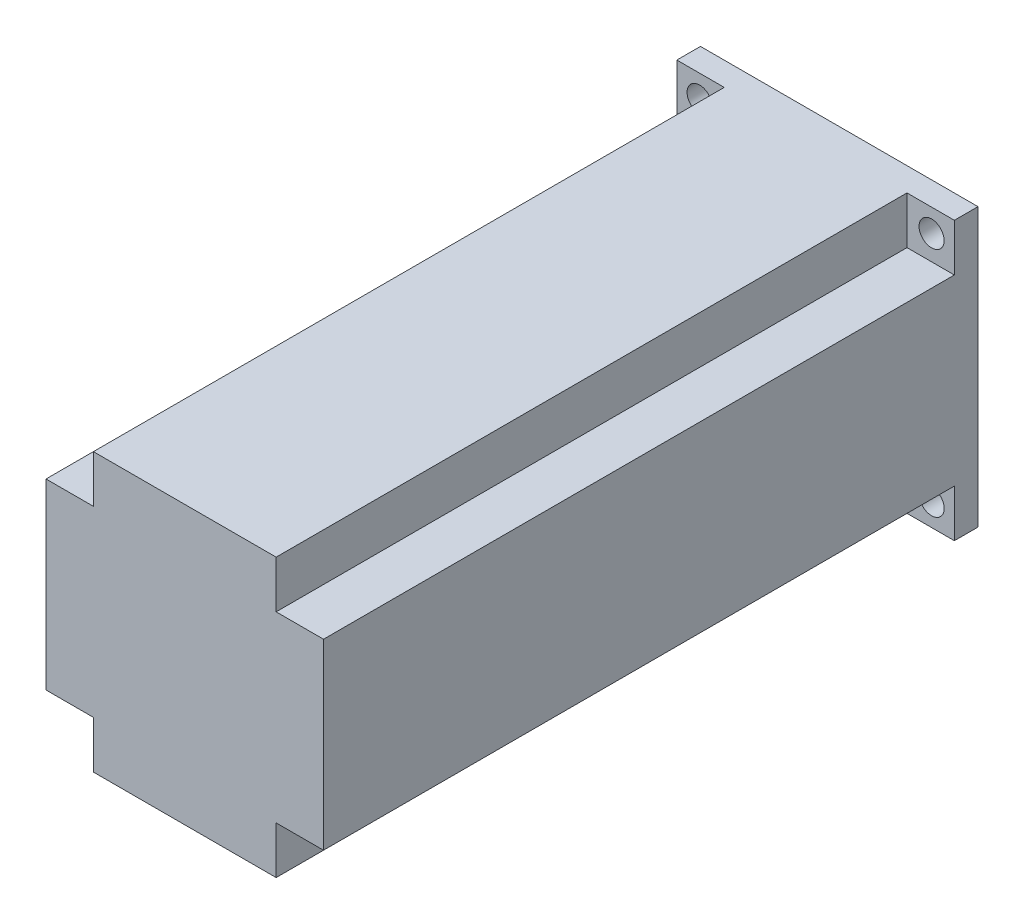
SolidWorks part; units mm, degrees
ref_plane "前视基准面" through (0, 0, 0) normal (0, 0, 1) x (1, 0, 0)
ref_plane "上视基准面" through (0, 0, 0) normal (0, 1, 0) x (1, 0, 0)
ref_plane "右视基准面" through (0, 0, 0) normal (1, 0, 0) x (0, 0, -1)
sketch "草图1" plane through (0, 0, 0) normal (0, 0, 1) x (1, 0, 0)
  line L1 (-23.57, 23.57) -> (23.57, 23.57) construction
  line L2 (-23.57, 23.57) -> (-23.57, -23.57) construction
  line L3 (-23.57, -23.57) -> (23.57, -23.57) construction
  line L4 (23.57, 23.57) -> (23.57, -23.57) construction
  line L5 (-23.57, 23.57) -> (23.57, -23.57) construction
  line L6 (-23.57, -23.57) -> (23.57, 23.57) construction
  line L7 (-28.2, 28.2) -> (28.2, 28.2)
  line L8 (-28.2, 28.2) -> (-28.2, -28.2)
  line L9 (-28.2, -28.2) -> (28.2, -28.2)
  line L10 (28.2, 28.2) -> (28.2, -28.2)
  line L11 (-28.2, 28.2) -> (28.2, -28.2) construction
  line L12 (-28.2, -28.2) -> (28.2, 28.2) construction
  circle A0 centre (23.57, 23.57) radius 2.55
  circle A1 centre (23.57, -23.57) radius 2.55
  circle A2 centre (-23.57, -23.57) radius 2.55
  circle A3 centre (-23.57, 23.57) radius 2.55
  point P0 (0, 0)
  point P7 (0, 0)
  dimension "D2" = 5.1
  dimension "D1" = 47.14
  dimension "D4" = 56.4
  dimension "D3" = 4
extrude "凸台-拉伸1" add sketch "草图1" along normal blind 133
sketch "草图2" plane through (0, 0, 133) normal (0, 0, 1) x (1, 0, 0)
  line L0 (-23.57, -23.57) -> (23.57, 23.57) construction
  line L5 (-28.57, 28.57) -> (-18.57, 28.57)
  line L6 (-28.57, 28.57) -> (-28.57, 18.57)
  line L7 (-28.57, 18.57) -> (-18.57, 18.57)
  line L8 (-18.57, 28.57) -> (-18.57, 18.57)
  line L9 (-28.57, 28.57) -> (-18.57, 18.57) construction
  line L10 (-28.57, 18.57) -> (-18.57, 28.57) construction
  line L11 (28.57, 28.57) -> (28.57, 18.57)
  line L12 (28.57, 28.57) -> (18.57, 28.57)
  line L13 (18.57, 28.57) -> (18.57, 18.57)
  line L14 (28.57, 18.57) -> (18.57, 18.57)
  line L15 (28.57, 28.57) -> (18.57, 18.57) construction
  line L16 (18.57, 28.57) -> (28.57, 18.57) construction
  line L17 (28.57, -28.57) -> (18.57, -28.57)
  line L18 (28.57, -28.57) -> (28.57, -18.57)
  line L19 (28.57, -18.57) -> (18.57, -18.57)
  line L20 (18.57, -28.57) -> (18.57, -18.57)
  line L21 (28.57, -28.57) -> (18.57, -18.57) construction
  line L22 (28.57, -18.57) -> (18.57, -28.57) construction
  line L23 (-28.57, -28.57) -> (-28.57, -18.57)
  line L24 (-28.57, -28.57) -> (-18.57, -28.57)
  line L25 (-18.57, -28.57) -> (-18.57, -18.57)
  line L26 (-28.57, -18.57) -> (-18.57, -18.57)
  line L27 (-28.57, -28.57) -> (-18.57, -18.57) construction
  line L28 (-18.57, -28.57) -> (-28.57, -18.57) construction
  point P0 (-23.57, 23.57)
  point P12 (23.57, 23.57)
  point P17 (23.57, -23.57)
  point P22 (-23.57, -23.57)
  circle M5 centre (-23.57, -23.57) radius 2.55
  circle M6 centre (23.57, 23.57) radius 2.55
  line M7 (28.2, -28.2) -> (28.2, 28.2)
  line M8 (28.2, 28.2) -> (-28.2, 28.2)
  line M9 (-28.2, 28.2) -> (-28.2, -28.2)
  line M10 (-28.2, -28.2) -> (28.2, -28.2)
  circle M11 centre (23.57, -23.57) radius 2.55
  dimension "D1" = 10
  dimension "D2" = 4
extrude "切除-拉伸1" cut sketch "草图2" against normal blind 128.2 contours L26 L25 M9 M10 M5 | L20 L19 M10 M7 M11 | L14 L13 M7 M8 M6 | L5 L8 L7 L6
sketch "草图3" plane through (0, 0, 0) normal (0, 0, -1) x (-1, 0, 0)
  circle A0 centre (0, 0) radius 4
  dimension "D1" = 8
extrude "凸台-拉伸2" add sketch "草图3" along normal blind 20.6
sketch "草图4" plane through (0, 0, 0) normal (0, 0, -1) x (-1, 0, 0)
  circle A0 centre (0, 0) radius 19.05
  dimension "D1" = 38.1
extrude "凸台-拉伸3" add sketch "草图4" along normal blind 1.6
